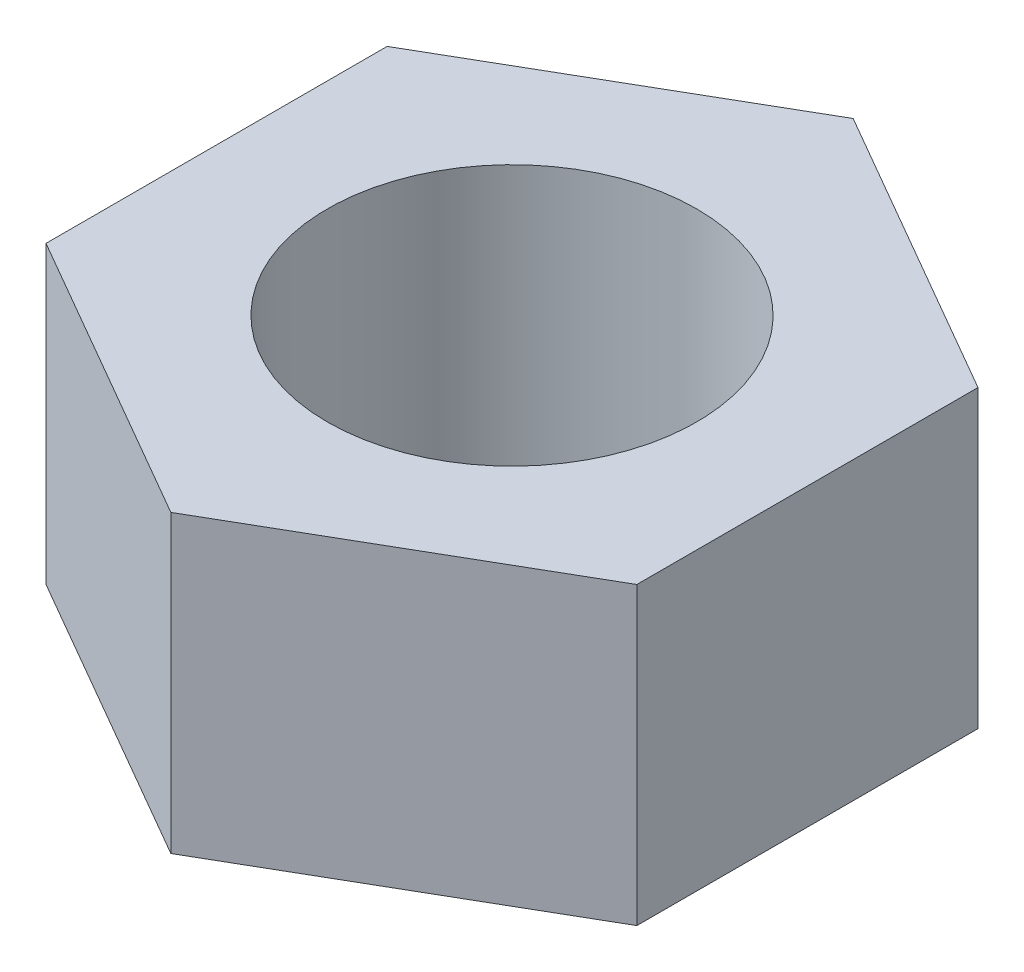
SolidWorks part; units mm, degrees
ref_plane "Спереди" through (0, 0, 0) normal (0, 0, 1) x (1, 0, 0)
ref_plane "Сверху" through (0, 0, 0) normal (0, 1, 0) x (1, 0, 0)
ref_plane "Справа" through (0, 0, 0) normal (1, 0, 0) x (0, 0, -1)
sketch "Эскиз1" plane through (0, 0, 0) normal (0, 1, 0) x (1, 0, 0)
  line L1 (0, -4.6188) -> (4, -2.3094)
  line L2 (4, -2.3094) -> (4, 2.3094)
  line L3 (4, 2.3094) -> (0, 4.6188)
  line L4 (0, 4.6188) -> (-4, 2.3094)
  line L5 (-4, 2.3094) -> (-4, -2.3094)
  line L6 (-4, -2.3094) -> (0, -4.6188)
  circle A0 centre (0, 0) radius 4 construction
  circle A1 centre (0, 0) radius 2.5
extrude "Вытянуть1" add sketch "Эскиз1" along normal blind 4
